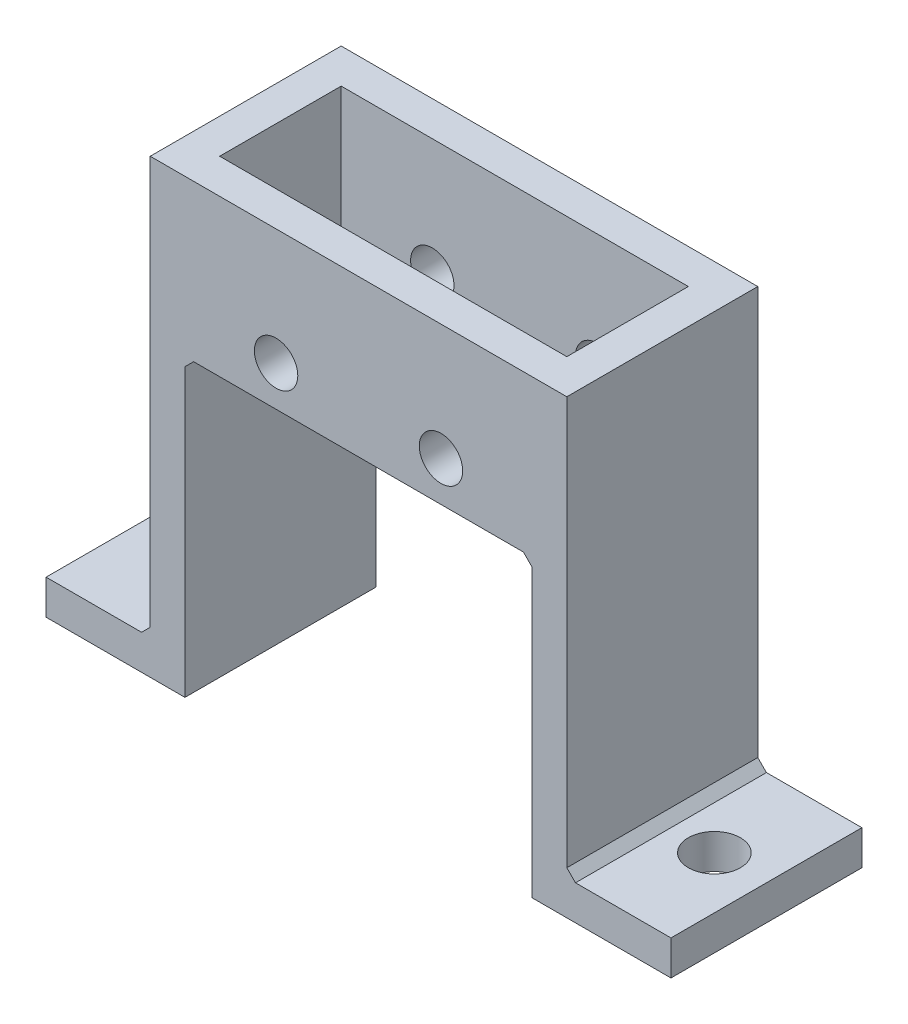
SolidWorks part; units mm, degrees
ref_plane "Alzado" through (0, 0, 0) normal (0, 0, 1) x (1, 0, 0)
ref_plane "Planta" through (0, 0, 0) normal (0, 1, 0) x (1, 0, 0)
ref_plane "Vista lateral" through (0, 0, 0) normal (1, 0, 0) x (0, 0, -1)
sketch "Croquis1" plane through (0, 0, 0) normal (0, 0, 1) x (1, 0, 0)
  line L0 (0, 0) -> (20, 0)
  line L1 (20, 0) -> (20, 10)
  line L2 (20, 0) -> (10, 0) construction
  line L3 (10, 0) -> (10, 2.3) construction
  line L4 (5.25, 2.3) -> (14.75, 2.3)
  line L5 (20, 10) -> (0, 10)
  line L6 (0, 10) -> (0, 0)
  circle A0 centre (5.25, 2.3) radius 1.25
  circle A1 centre (14.75, 2.3) radius 1.25
  point P9 (10, 2.3)
  dimension "D4" = 2.5
  dimension "D5" = 2.5
  dimension "D1" = 20
  dimension "D2" = 2.3
  dimension "D3" = 9.5
  dimension "D6" = 10
extrude "Saliente-Extruir1" add sketch "Croquis1" along normal blind 2 contours L6 L0 L1 L5 | A0 | A1
sketch "Croquis2" plane through (0, 0, 2) normal (0, 0, 1) x (1, 0, 0)
  line L0 (0, 10) -> (-2, 10)
  line L1 (-2, 10) -> (-2, 0)
  line L2 (-2, 0) -> (0, 0)
  line L3 (20, 10) -> (22, 10)
  line L4 (22, 10) -> (22, 0)
  line L5 (22, 0) -> (20, 0)
  line L6 (0, 10) -> (0, 0)
  line L7 (20, 10) -> (20, 0)
  dimension "D1" = 2
  dimension "D2" = 2
extrude "Saliente-Extruir2" add sketch "Croquis2" against normal blind 11
sketch "Croquis3" plane through (0, 0, -9) normal (0, 0, -1) x (-1, 0, 0)
  line L1 (-20, 10) -> (0, 10)
  line L2 (-20, 10) -> (-20, 0)
  line L3 (-20, 0) -> (0, 0)
  line L4 (0, 10) -> (0, 0)
  circle A0 centre (-5.25, 2.3) radius 1.25 construction
  circle A1 centre (-14.75, 2.3) radius 1.25 construction
  circle A2 centre (-5.25, 2.3) radius 1.25
  circle A3 centre (-14.75, 2.3) radius 1.25
extrude "Saliente-Extruir3" add sketch "Croquis3" against normal blind 2 separate body
sketch "Croquis4" plane through (0, 0, 0) normal (0, -1, 0) x (1, 0, 0)
  line L1 (-2, 2) -> (0, 2)
  line L2 (-2, 2) -> (-2, -9)
  line L3 (-2, -9) -> (0, -9)
  line L4 (0, 2) -> (0, -9)
  line L5 (22, 2) -> (20, 2)
  line L6 (22, 2) -> (22, -9)
  line L7 (22, -9) -> (20, -9)
  line L8 (20, 2) -> (20, -9)
extrude "Saliente-Extruir4" add sketch "Croquis4" along normal blind 17
sketch "Croquis5" plane through (22, 0, 0) normal (1, 0, 0) x (0, 0, -1)
  line L0 (9, -17) -> (9, 10) construction
  line L1 (-2, -17) -> (9, -17)
  line L2 (-2, -17) -> (-2, -15)
  line L3 (-2, -15) -> (9, -15)
  line L4 (9, -17) -> (9, -15)
  dimension "D1" = 2
extrude "Saliente-Extruir5" add sketch "Croquis5" along normal blind 6
sketch "Croquis6" plane through (-2, 0, 0) normal (-1, 0, 0) x (0, 0, 1)
  line L0 (2, 10) -> (2, -17) construction
  line L1 (-9, -17) -> (2, -17)
  line L2 (-9, -17) -> (-9, -15)
  line L3 (-9, -15) -> (2, -15)
  line L4 (2, -17) -> (2, -15)
  dimension "D1" = 2
extrude "Saliente-Extruir6" add sketch "Croquis6" along normal blind 6
sketch "Croquis7" plane through (0, 10, 0) normal (0, 1, 0) x (1, 0, 0)
  line L1 (-2, 9) -> (22, 9)
  line L2 (-2, 9) -> (-2, -2)
  line L3 (-2, -2) -> (22, -2)
  line L4 (22, 9) -> (22, -2)
  line L5 (20, 0) -> (0, 0)
  line L6 (20, 0) -> (20, 7)
  line L7 (20, 7) -> (0, 7)
  line L8 (0, 0) -> (0, 7)
extrude "Cortar-Extruir1" cut sketch "Croquis7" against normal blind 1
sketch "Croquis8" plane through (0, -15, 0) normal (0, 1, 0) x (1, 0, 0)
  line L0 (-8, 9) -> (-2, 9) construction
  line L1 (-2, 9) -> (-5, 9) construction
  line L2 (-5, 9) -> (-5, -2) construction
  line L3 (-8, -2) -> (-2, -2) construction
  line L4 (-5, -2) -> (-5, 3.5) construction
  line L5 (22, 9) -> (28, 9) construction
  line L6 (28, 9) -> (22, 9) construction
  line L7 (28, 9) -> (25, 9) construction
  line L8 (25, 9) -> (25, -2) construction
  line L9 (28, -2) -> (22, -2) construction
  line L10 (25, -2) -> (25, 3.5) construction
  circle A0 centre (-5, 3.5) radius 1.5
  circle A1 centre (25, 3.5) radius 1.5
  dimension "D1" = 3
  dimension "D2" = 3
extrude "Cortar-Extruir2" cut sketch "Croquis8" against normal blind 11
chamfer "Chaflán1" distance 0.5 angle 45 6 edges at (0, 0, -8) (0, 0, 1) (20, 0, 1) (20, 0, -8) (-2, -15, -3.5) (22, -15, -3.5)
